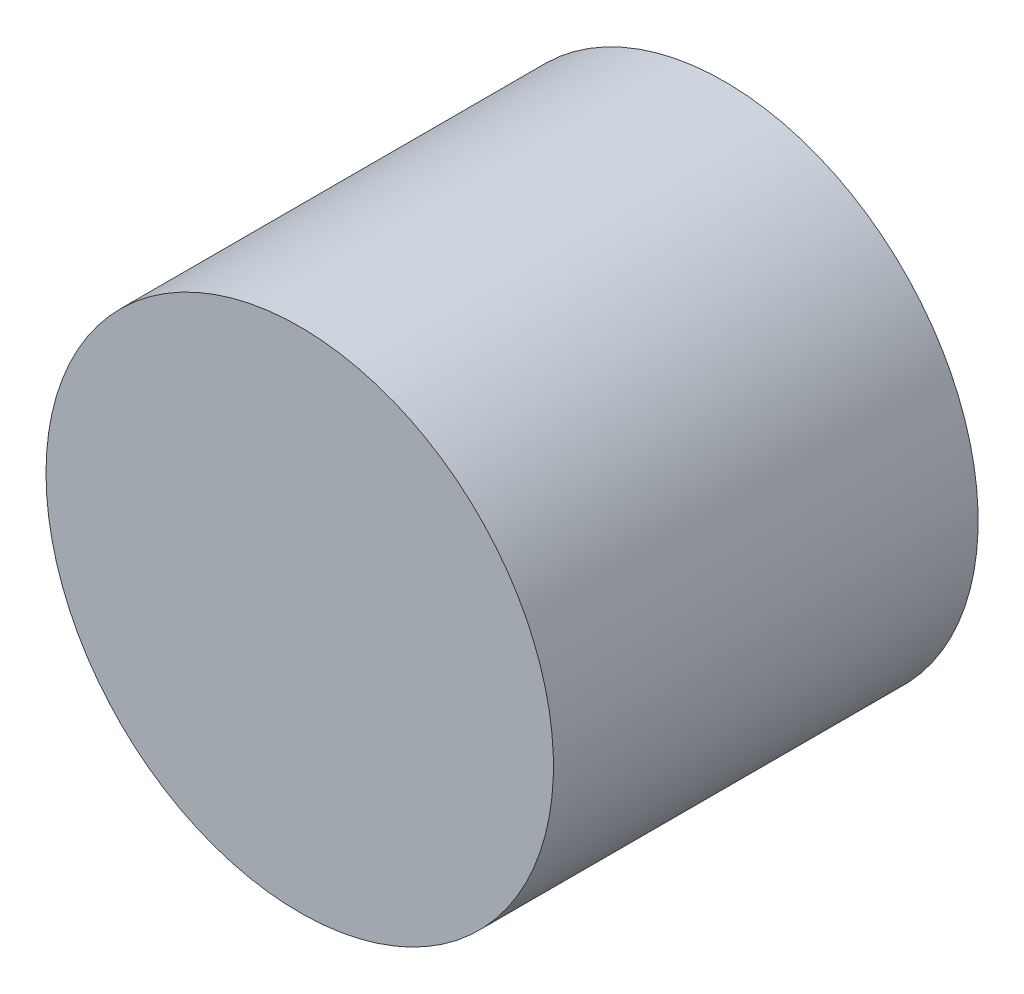
SolidWorks part; units mm, degrees
ref_plane "Plane1" through (0, 0, 0) normal (0, 0, 1) x (1, 0, 0)
ref_plane "Plane2" through (0, 0, 0) normal (0, 1, 0) x (1, 0, 0)
ref_plane "Plane3" through (0, 0, 0) normal (1, 0, 0) x (0, 0, -1)
sketch "Sketch1" plane through (0, 0, 0) normal (0, 0, 1) x (1, 0, 0)
  circle A0 centre (-0.7394, 0.6843) radius 4.6 construction
  circle A2 centre (-0.7394, 0.6843) radius 4.6
extrude "rubber feet" add sketch "Sketch1" along normal blind 7.7
